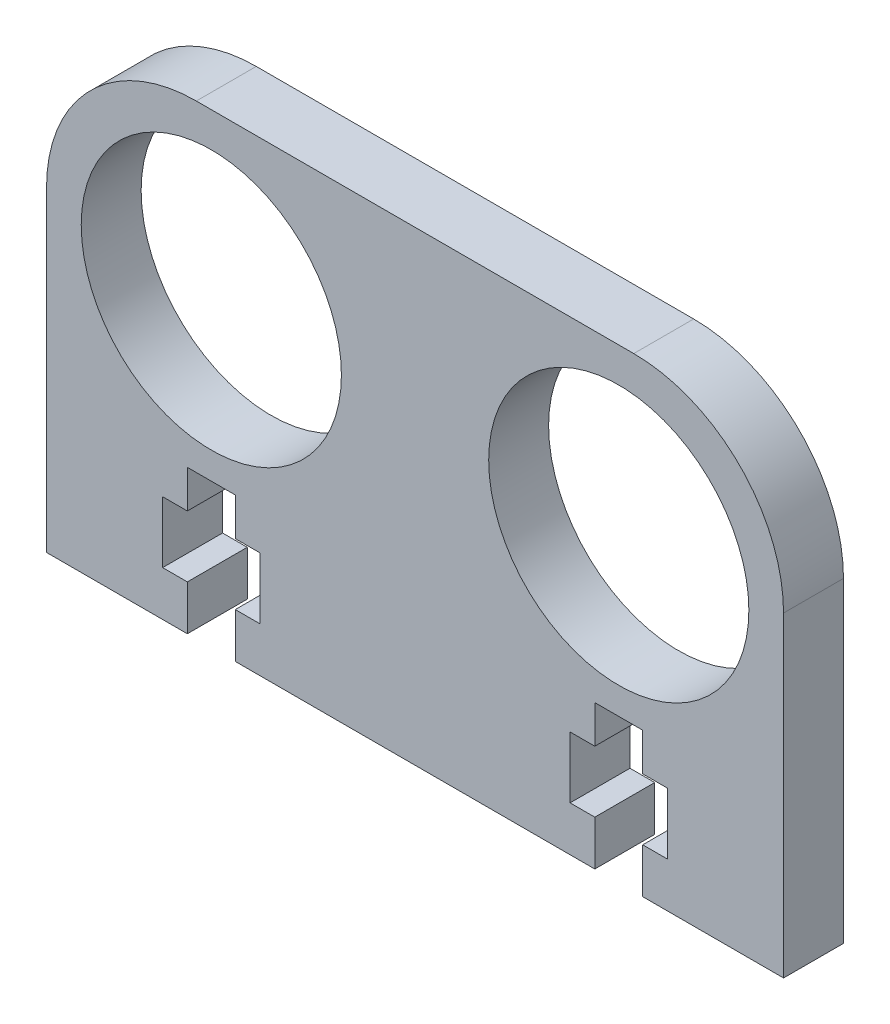
SolidWorks part; units mm, degrees
material "Balsa"
ref_plane "Plano frontal" through (0, 0, 0) normal (0, 0, 1) x (1, 0, 0)
ref_plane "Plano superior" through (0, 0, 0) normal (0, 1, 0) x (1, 0, 0)
ref_plane "Plano direito" through (0, 0, 0) normal (1, 0, 0) x (0, 0, -1)
sketch "Esboço1" plane through (0, 0, 0) normal (0, 0, 1) x (1, 0, 0)
  line L0 (-11.2, -16.1) -> (-11.2, -18.5263)
  line L1 (-16.05, -12) -> (-14.4, -12)
  line L2 (-14.4, -12) -> (-14.4, -9.4767)
  line L3 (-11.2, -12) -> (-11.2, -9.4767)
  line L4 (15.4, 12) -> (-13.8, 12)
  line L6 (-23.8, -19.1) -> (-23.8, 2)
  line L7 (25.4, -19.1) -> (25.4, 2)
  line L8 (-16.05, -16.1) -> (-14.4, -16.1)
  line L9 (-14.4, -16.1) -> (-14.4, -19.1)
  line L10 (17.65, -12) -> (17.65, -16.1)
  line L11 (11.15, -12) -> (11.15, -16.1)
  line L12 (-9.55, -16.1) -> (-9.55, -12)
  line L13 (16, -16.1) -> (16, -18.5263)
  line L14 (12.8, -16.1) -> (12.8, -18.5263)
  line L15 (-16.05, -16.1) -> (-16.05, -12)
  line L16 (-14.4, -9.4767) -> (-11.2, -9.4767)
  line L17 (-11.2, -12) -> (-9.55, -12)
  line L18 (12.8, -12) -> (12.8, -9.4767)
  line L19 (-23.8, -12) -> (23.8, -12) construction
  line L20 (16, -12) -> (16, -9.4767)
  line L21 (12.8, -9.4767) -> (16, -9.4767)
  line L22 (11.15, -12) -> (12.8, -12)
  line L23 (11.15, -16.1) -> (12.8, -16.1)
  line L24 (16, -12) -> (17.65, -12)
  line L25 (-23.8, -16.1) -> (23.8, -16.1) construction
  line L26 (16, -16.1) -> (17.65, -16.1)
  line L27 (-11.2, -16.1) -> (-9.55, -16.1)
  line L28 (-14.4, -19.1) -> (-23.8, -19.1)
  line L29 (12.8, -19.1) -> (-11.2, -19.1)
  line L30 (-11.2, -18.5263) -> (-11.2, -19.1)
  line L31 (12.8, -18.5263) -> (12.8, -19.1)
  line L32 (16, -18.5263) -> (16, -19.1)
  line L33 (16, -19.1) -> (25.4, -19.1)
  circle A0 centre (-12.8, 1) radius 8.05
  circle A1 centre (14.4, 1) radius 8.05
  arc A2 (15.4, 12) -> (25.4, 2) centre (15.4, 2) cw
  arc A3 (-13.8, 12) -> (-23.8, 2) centre (-13.8, 2) ccw
  point P17 (-14.4, 0)
  point P22 (-12.8, -12)
  point P28 (-12.8, -18.5263)
  point P30 (-11.2, 0)
  point P37 (-9.55, -18.5263)
  point P39 (-16.05, -18.5263)
  dimension "D3" = 19.1
  dimension "D4" = 19.1
  dimension "D1" = 21.1
  dimension "D2" = 19.1
  dimension "D5" = 11
  dimension "D9" = 16.1
  dimension "D10" = 16.1
  dimension "D6" = 3
  dimension "D7" = 11
  dimension "D8" = 4.1
extrude "Ressalto-extrusão1" add sketch "Esboço1" along normal blind 4
scale "Escala1" scale about centroid uniform scaling yes scale factor 0.95
sketch "Esboço2" plane through (0, 0, 0.1) normal (0, 0, -1) x (-1, 0, 0)
  line L0 (0, 0) -> (-5.508, -0.0931)
  line L1 (0, 0) -> (0, 5.695)
  line L2 (0, 0) -> (3.9062, -0.0741)
  circle A0 centre (-13.72, 0.6979) radius 8.25
  circle A1 centre (12.12, 0.6979) radius 8.25
  circle M2 centre (12.12, 0.6979) radius 7.6475
  circle M3 centre (-13.72, 0.6979) radius 7.6475
  dimension "D1" = 16.5
  dimension "D2" = 16.5
extrude "Corte-extrusão1" cut sketch "Esboço2" against normal blind 10 contours A1 M2 | A0 M3
